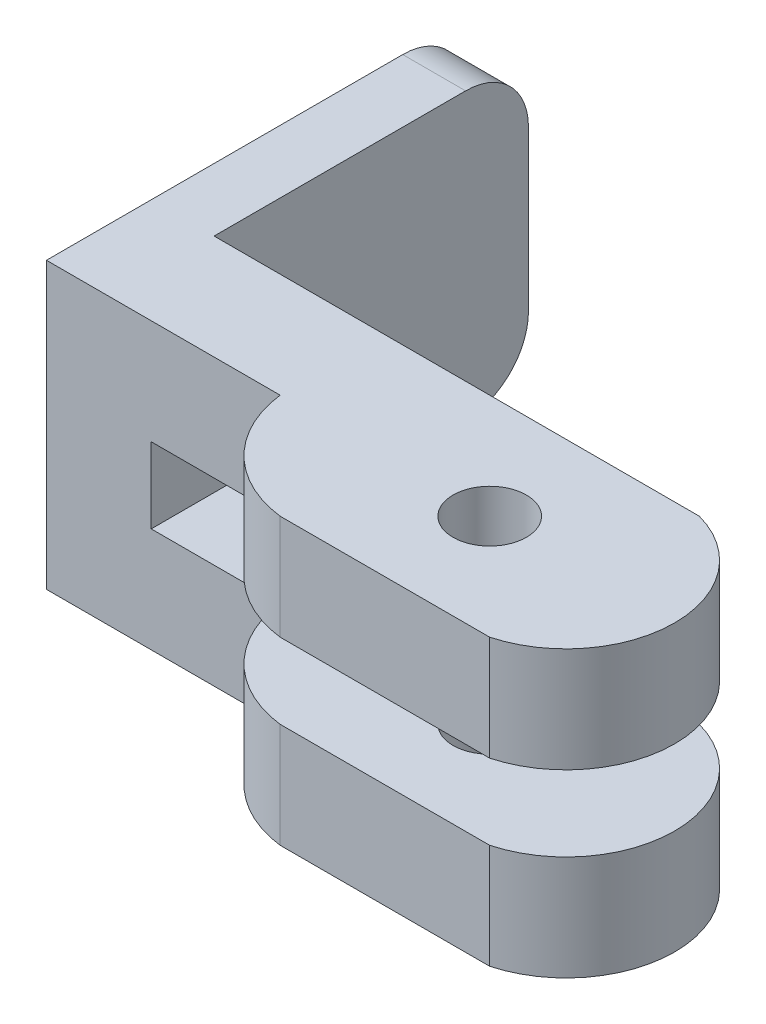
SolidWorks part; units mm, degrees
ref_plane "Alzado" through (0, 0, 0) normal (0, 0, 1) x (1, 0, 0)
ref_plane "Planta" through (0, 0, 0) normal (0, 1, 0) x (1, 0, 0)
ref_plane "Vista lateral" through (0, 0, 0) normal (1, 0, 0) x (0, 0, -1)
sketch "Croquis1" plane through (0, 0, 0) normal (0, 0, 1) x (1, 0, 0)
  line L0 (0, 0) -> (-90, 0) construction
  line L1 (-90, -6.8) -> (-90, -1.8)
  line L2 (-90, -1.8) -> (-65, -1.8)
  line L3 (-65, -1.8) -> (-65, 1.8)
  line L4 (-90, -6.8) -> (90, -6.8)
  line L5 (0, 0) -> (0, -28.0002) construction
  line L6 (-90, 6.8) -> (-90, 1.8)
  line L7 (-90, 1.8) -> (-65, 1.8)
  line L8 (-90, 6.8) -> (90, 6.8)
  line L9 (90, 6.8) -> (90, 1.8)
  line L10 (90, 1.8) -> (65, 1.8)
  line L11 (65, -1.8) -> (65, 1.8)
  line L12 (90, -6.8) -> (90, -1.8)
  line L13 (90, -1.8) -> (65, -1.8)
  point P10 (-65, 0)
  point P14 (0, 6.8)
  point P19 (0, -6.8)
  dimension "D1" = 90
  dimension "D2" = 5
  dimension "D3" = 1.8
  dimension "D4" = 25
  dimension "D5" = 13.6
extrude "Saliente-Extruir1" add sketch "Croquis1" along normal blind 10
sketch "Croquis2" plane through (0, 6.8, 0) normal (0, 1, 0) x (1, 0, 0)
  line L0 (0, -10) -> (0, 0) construction
  line L1 (90, -10) -> (-90, -10) construction
  line L2 (-91.25, -5) -> (90, -5) construction
  line L4 (90, -10) -> (90, 0) construction
  line L6 (-81.15, -3.15) -> (-81.15, -6.3963) construction
  line L8 (-86.15, -10) -> (-86.15, 0) construction
  line L9 (90, 0) -> (-90, 0) construction
  line L10 (-86.15, 0) -> (-90, 0)
  line L11 (-90, 0) -> (-90, -10)
  line L12 (-90, -10) -> (-86.15, -10)
  line L13 (86.15, -10) -> (86.15, 0) construction
  line L15 (90, -10) -> (86.15, -10)
  line L16 (90, 0) -> (90, -10)
  line L17 (86.15, 0) -> (90, 0)
  line L20 (-71.15, -5) -> (71.15, -5)
  line L21 (-76.15, -10) -> (76.15, -10)
  circle A0 centre (-81.15, -5) radius 1.75
  circle A1 centre (81.15, -5) radius 1.75
  arc A2 (-86.15, 0) -> (-86.15, -10) centre (-84.7917, -5) ccw
  arc A3 (86.15, 0) -> (86.15, -10) centre (84.7917, -5) cw
  arc A6 (-76.15, -10) -> (-71.15, -5) centre (-76.8383, -4.3117) ccw
  arc A7 (76.15, -10) -> (71.15, -5) centre (76.8383, -4.3117) cw
  point P7 (-90, -5)
  point P20 (-81.15, -6.85)
  point P52 (0, -5)
  dimension "D2" = 3.5
  dimension "D1" = 8.85
  dimension "D5" = 5
extrude "Cortar-Extruir1" cut sketch "Croquis2" against normal through all
sketch "Croquis3" plane through (0, 0, 0) normal (0, 0, -1) x (-1, 0, 0)
  line L0 (0, 0) -> (0, 22.1197) construction
  line L1 (-86.15, 6.8) -> (86.15, 6.8) construction
  line L2 (-63, 6.8) -> (-60, 6.8)
  line L3 (-63, 6.8) -> (-63, -6.8)
  line L4 (-63, -6.8) -> (-60, -6.8)
  line L5 (-60, 6.8) -> (-60, -6.8)
  line L6 (86.15, -6.8) -> (-86.15, -6.8) construction
  line L7 (-65, -1.8) -> (-65, 1.8) construction
  line L8 (63, 6.8) -> (63, -6.8)
  line L9 (63, -6.8) -> (60, -6.8)
  line L10 (60, 6.8) -> (60, -6.8)
  point P17 (60, 0)
  line M1 (86.15, 6.8) -> (-86.15, 6.8)
  line M7 (-86.15, -6.8) -> (86.15, -6.8)
  dimension "D1" = 3
  dimension "D2" = 2
  dimension "D3" = 120
extrude "Saliente-Extruir2" add sketch "Croquis3" along normal blind 15 contours L5 L3 M1 M7 | L10 L8 M1 M7
chamfer "Chaflán1" distance 10 angle 15 1 edges at (0, -6.8, 0)
fillet "Redondeo1" radius 3 4 edges at (-61.5, 6.8, -15) (-61.5, -6.8, -15) (61.5, 6.8, -15) (61.5, -6.8, -15)
sketch "Croquis4" plane through (0, -6.8, 0) normal (0, -1, 0) x (-1, 0, 0)
  line L0 (-60, -24.3358) -> (-60, 22.7022)
  line L1 (-60, 12) -> (-60, -2.6795) construction
  line L2 (-60, -24.3358) -> (106.7226, -24.3358)
  line L3 (106.7226, -24.3358) -> (106.7226, 22.7022)
  line L4 (106.7226, 22.7022) -> (-60, 22.7022)
  point P4 (-60, 4.6603)
  point P5 (106.7226, 22.7022)
extrude "Cortar-Extruir2" cut sketch "Croquis4" against normal through all
